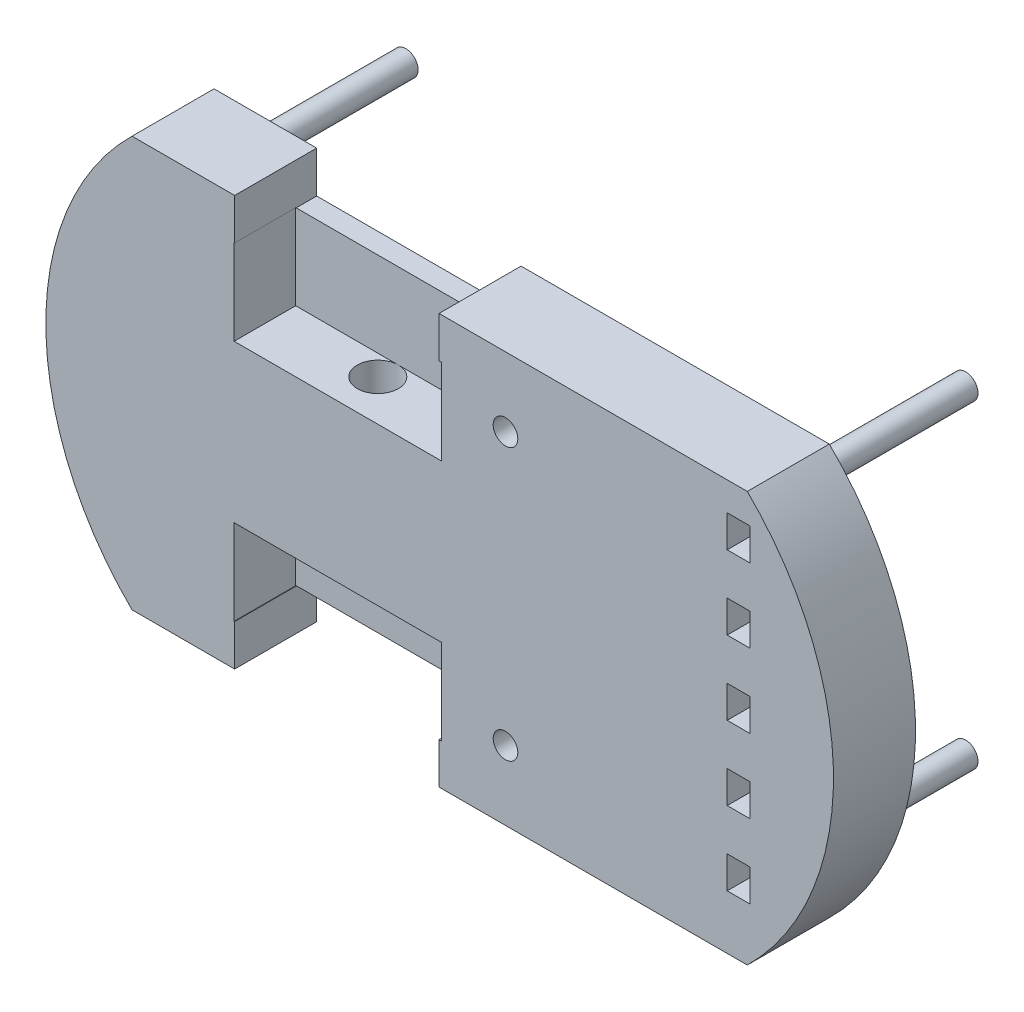
SolidWorks part; units mm, degrees
ref_plane "Front Plane" through (0, 0, 0) normal (0, 0, 1) x (1, 0, 0)
ref_plane "Top Plane" through (0, 0, 0) normal (0, 1, 0) x (1, 0, 0)
ref_plane "Right Plane" through (0, 0, 0) normal (1, 0, 0) x (0, 0, -1)
sketch "Sketch1" plane through (0, 0, 0) normal (0, 0, 1) x (1, 0, 0)
  line L1 (-26, 49.2143) -> (-41, 49.2143)
  line L2 (-26, 49.2143) -> (-26, 39.2143)
  line L3 (-26, 39.2143) -> (-41, 39.2143)
  line L4 (-41, 49.2143) -> (-41, 39.2143)
  line L5 (-26, 49.2143) -> (-41, 39.2143) construction
  line L6 (-26, 39.2143) -> (-41, 49.2143) construction
  arc A0 (-26, 49.2143) -> (-26, 39.2143) centre (-30.899, 44.2143) cw
  arc A1 (-41, 49.2143) -> (-41, 39.2143) centre (-36.101, 44.2143) ccw
  dimension "D10" = 7
  dimension "D11" = 7
  dimension "D1" = 0
  dimension "D2" = 10
  dimension "D3" = 0
  dimension "D4" = 0
  dimension "D5" = 0
  dimension "D6" = 0
  dimension "D7" = 0
  dimension "D8" = 0
  dimension "D9" = 0
extrude "Boss-Extrude1" add sketch "Sketch1" along normal blind 2 contours L4 A1 | L1 L4 L3 L2 | A0 L2
sketch "Sketch2" plane through (0, 0, 2) normal (0, 0, 1) x (1, 0, 0)
  line L0 (-44.1776, 44.2143) -> (-22.1088, 44.2143) construction
  line L1 (-26, 49.2143) -> (-41, 49.2143) construction
  line L2 (-38.4976, 40.226) -> (-33.5148, 40.226)
  line L3 (-38.4976, 49.3919) -> (-33.5148, 49.3919)
  line L4 (-38.4976, 49.3919) -> (-38.4976, 48.2026)
  line L5 (-38.4976, 48.2026) -> (-33.5148, 48.2026)
  line L6 (-33.5148, 49.3919) -> (-33.5148, 48.2026)
  line L7 (-33.5148, 39.0367) -> (-33.5148, 40.226)
  line L8 (-38.4976, 39.0367) -> (-33.5148, 39.0367)
  line L9 (-38.4976, 39.0367) -> (-38.4976, 40.226)
  dimension "D1" = 5
extrude "Cut-Extrude1" cut sketch "Sketch2" against normal through all both and the other way through all
sketch "Sketch3" plane through (0, 0, 2) normal (0, 0, 1) x (1, 0, 0)
  line L0 (-44.8953, 44.2143) -> (-20.1247, 44.2143) construction
  line L1 (-38.4976, 49.2143) -> (-41, 49.2143) construction
  line L2 (-33.5, 50.4377) -> (-33.5, 36.2912) construction
  circle A0 centre (-31.8949, 47.5259) radius 0.3
  circle A1 centre (-31.8949, 40.9027) radius 0.3
  dimension "D3" = 0.6
  dimension "D1" = 5
  dimension "D2" = 7.5
extrude "Cut-Extrude2" cut sketch "Sketch3" against normal through all both
sketch "Sketch4" plane through (0, 0, 0) normal (0, 0, -1) x (-1, 0, 0)
  line L0 (18.2798, -19.2667) -> (42.9975, -21.4292) construction
  line L2 (22.487, 44.2143) -> (46.5768, 44.2143) construction
  line L3 (26, 49.2143) -> (33.5148, 49.2143) construction
  line L4 (33.5, 50.9442) -> (33.5, 37.8533) construction
  circle A0 centre (26.6754, 48.1014) radius 0.3
  circle A1 centre (26.6754, 40.3272) radius 0.3
  circle A2 centre (40.3246, 40.3272) radius 0.3
  circle A3 centre (40.3246, 48.1014) radius 0.3
  dimension "D3" = 0.6
  dimension "D1" = 5
  dimension "D2" = 7.5
extrude "Boss-Extrude2" add sketch "Sketch4" along normal blind 4
sketch "Sketch5" plane through (0, 40.226, 0) normal (0, -1, 0) x (1, 0, 0)
  line L0 (-33.5148, 2) -> (-38.4976, 2) construction
  line L2 (-38.4976, 0) -> (-38.4976, 2) construction
  circle A0 centre (-36.0076, 1) radius 0.5
  dimension "D3" = 1
  dimension "D1" = 1
  dimension "D2" = 2.49
extrude "Cut-Extrude3" cut sketch "Sketch5" against normal through all both and the other way through all
sketch "Sketch6" plane through (0, 0, 0) normal (0, 0, -1) x (-1, 0, 0)
  line L5 (27.772, 47.2552) -> (30.4877, 47.2552)
  line L6 (27.772, 47.2552) -> (27.772, 41.0429)
  line L7 (27.772, 41.0429) -> (30.4877, 41.0429)
  line L8 (30.4877, 47.2552) -> (30.4877, 41.0429)
  line L9 (27.4347, 47.6635) -> (30.4877, 47.6635)
  line L10 (27.4347, 47.6635) -> (27.4347, 40.6434)
  line L11 (27.4347, 40.6434) -> (30.4877, 40.6434)
  line L12 (30.4877, 47.6635) -> (30.4877, 40.6434)
extrude "Boss-Extrude4" add sketch "Sketch6" along normal blind 1 contours L12 L9 L10 L11 L7 L6 L5
fillet "Fillet4" radius 0.1 8 edges at (-29.1298, 47.2552, -1) (-27.772, 44.149, -1) (-29.1298, 41.0429, -1) (-30.4877, 40.8431, -1) (-28.9612, 40.6434, -1) (-27.4347, 44.1534, -1) (-28.9612, 47.6635, -1) (-30.4877, 47.4594, -1)
sketch "Sketch8" plane through (0, 0, 0) normal (0, 0, -1) x (-1, 0, 0)
  line L30 (40.7914, 48.7143) -> (38.9976, 48.7143)
  line L31 (38.9976, 48.7143) -> (38.9976, 47.7026)
  line L32 (38.9976, 47.7026) -> (33.0148, 47.7026)
  line L33 (33.0148, 47.7026) -> (33.0148, 48.7143)
  line L34 (33.0148, 48.7143) -> (26.2086, 48.7143)
  line L35 (26.2086, 39.7143) -> (33.0148, 39.7143)
  line L36 (33.0148, 39.7143) -> (33.0148, 40.726)
  line L37 (33.0148, 40.726) -> (38.9976, 40.726)
  line L38 (38.9976, 40.726) -> (38.9976, 39.7143)
  line L39 (38.9976, 39.7143) -> (40.7914, 39.7143)
  line L40 (40.7914, 48.7143) -> (38.9976, 48.7143)
  line L41 (38.9976, 48.7143) -> (38.9976, 47.7026)
  line L42 (38.9976, 47.7026) -> (33.0148, 47.7026)
  line L43 (33.0148, 47.7026) -> (33.0148, 48.7143)
  line L44 (33.0148, 48.7143) -> (26.2086, 48.7143)
  line L45 (26.2086, 39.7143) -> (33.0148, 39.7143)
  line L46 (33.0148, 39.7143) -> (33.0148, 40.726)
  line L47 (33.0148, 40.726) -> (38.9976, 40.726)
  line L48 (38.9976, 40.726) -> (38.9976, 39.7143)
  line L49 (38.9976, 39.7143) -> (40.7914, 39.7143)
  arc A6 (26.2086, 48.7143) -> (26.2086, 39.7143) centre (30.899, 44.2143) ccw
  arc A7 (40.7914, 39.7143) -> (40.7914, 48.7143) centre (36.101, 44.2143) ccw
  arc A8 (26.2086, 48.7143) -> (26.2086, 39.7143) centre (30.899, 44.2143) ccw
  arc A9 (40.7914, 39.7143) -> (40.7914, 48.7143) centre (36.101, 44.2143) ccw
  dimension "D1" = 0.5
extrude "Cut-Extrude4" cut sketch "Sketch8" against normal blind 0.4
sketch "Sketch9" plane through (0, 0, 2) normal (0, 0, 1) x (1, 0, 0)
  line L0 (-45.3496, 44.2143) -> (-15.6382, 44.2143) construction
  line L1 (-38.5098, 48.211) -> (-33.4543, 48.211)
  line L2 (-38.5098, 48.211) -> (-38.5098, 46.1293)
  line L3 (-38.5098, 46.1293) -> (-33.4543, 46.1293)
  line L4 (-33.4543, 48.211) -> (-33.4543, 46.1293)
  line L5 (-26, 49.2143) -> (-33.5148, 49.2143) construction
  line L6 (-38.5098, 42.2993) -> (-33.4543, 42.2993)
  line L7 (-33.4543, 40.2176) -> (-33.4543, 42.2993)
  line L8 (-38.5098, 40.2176) -> (-33.4543, 40.2176)
  line L9 (-38.5098, 40.2176) -> (-38.5098, 42.2993)
  dimension "D1" = 5
extrude "Cut-Extrude5" cut sketch "Sketch9" against normal blind 1.5
sketch "Sketch10" plane through (0, 0, 2) normal (0, 0, 1) x (1, 0, 0)
  line L0 (-26.4901, 46.718) -> (-26.4901, 45.9363)
  line L1 (-26.4901, 48.518) -> (-25.9364, 48.518)
  line L2 (-26.4901, 48.518) -> (-26.4901, 47.7363)
  line L3 (-26.4901, 47.7363) -> (-25.9364, 47.7363)
  line L4 (-25.9364, 48.518) -> (-25.9364, 47.7363)
  line L5 (-26.4901, 46.718) -> (-25.9364, 46.718)
  line L6 (-25.9364, 46.718) -> (-25.9364, 45.9363)
  line L7 (-26.4901, 45.9363) -> (-25.9364, 45.9363)
  line L8 (-26.4901, 44.918) -> (-26.4901, 44.1363)
  line L9 (-26.4901, 44.918) -> (-25.9364, 44.918)
  line L10 (-25.9364, 44.918) -> (-25.9364, 44.1363)
  line L11 (-26.4901, 44.1363) -> (-25.9364, 44.1363)
  line L12 (-26.4901, 43.118) -> (-26.4901, 42.3363)
  line L13 (-26.4901, 43.118) -> (-25.9364, 43.118)
  line L14 (-25.9364, 43.118) -> (-25.9364, 42.3363)
  line L15 (-26.4901, 42.3363) -> (-25.9364, 42.3363)
  line L16 (-26.4901, 41.318) -> (-26.4901, 40.5363)
  line L17 (-26.4901, 41.318) -> (-25.9364, 41.318)
  line L18 (-25.9364, 41.318) -> (-25.9364, 40.5363)
  line L19 (-26.4901, 40.5363) -> (-25.9364, 40.5363)
  dimension "D1" = 5
extrude "Cut-Extrude7" cut sketch "Sketch10" against normal blind 1
